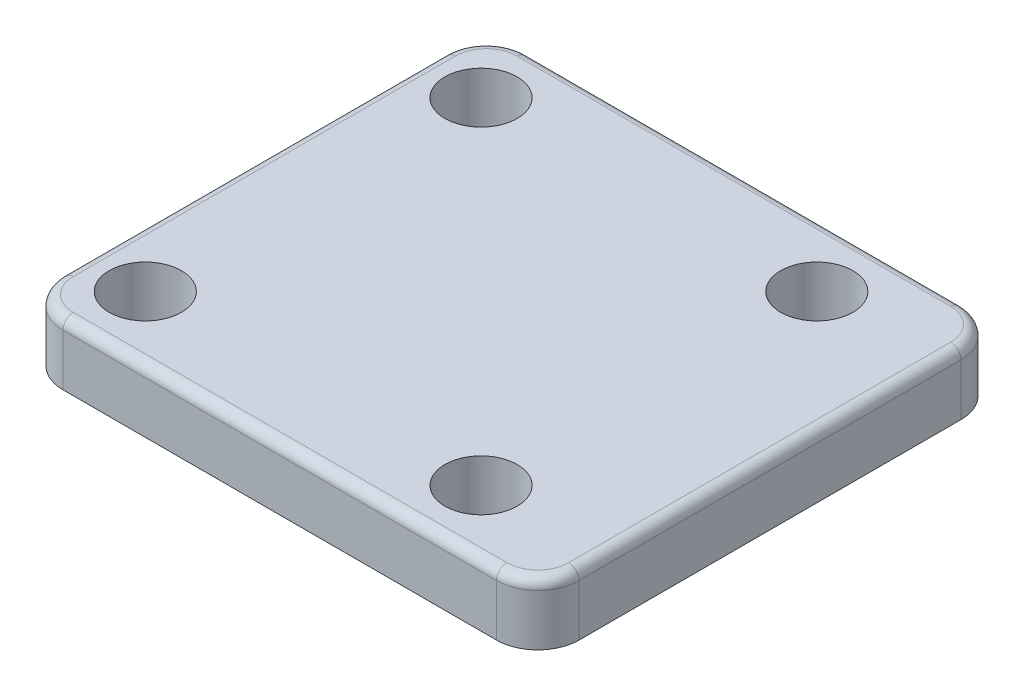
SolidWorks part; units mm, degrees
ref_plane "Front Plane" through (0, 0, 0) normal (0, 0, 1) x (1, 0, 0)
ref_plane "Top Plane" through (0, 0, 0) normal (0, 1, 0) x (1, 0, 0)
ref_plane "Right Plane" through (0, 0, 0) normal (1, 0, 0) x (0, 0, -1)
sketch "Sketch1" plane through (0, 0, 0) normal (0, 1, 0) x (1, 0, 0)
  line L1 (24, -22.5) -> (-18, -22.5)
  line L2 (28, -18.5) -> (28, 18.5)
  line L3 (24, 22.5) -> (-18, 22.5)
  line L4 (-22, -18.5) -> (-22, 18.5)
  line L5 (28, -22.5) -> (-22, 22.5) construction
  line L6 (28, 22.5) -> (-22, -22.5) construction
  arc A0 (24, -22.5) -> (28, -18.5) centre (24, -18.5) ccw
  arc A1 (-18, -22.5) -> (-22, -18.5) centre (-18, -18.5) cw
  arc A2 (28, 18.5) -> (24, 22.5) centre (24, 18.5) ccw
  arc A3 (-18, 22.5) -> (-22, 18.5) centre (-18, 18.5) ccw
  point P0 (3, 0)
  dimension "D5" = 4
  dimension "D1" = 50
  dimension "D2" = 45
  dimension "D3" = 22
  dimension "D4" = 22.5
extrude "Boss-Extrude1" add sketch "Sketch1" along normal blind 6
fillet "Fillet1" radius 1 8 edges at (3, 6, 22.5) (-20.8284, 6, 21.3284) (-22, 6, 0) (-20.8284, 6, -21.3284) (3, 6, -22.5) (26.8284, 6, -21.3284) (28, 6, 0) (26.8284, 6, 21.3284)
sketch "Sketch2" plane through (0, 6, 0) normal (0, 1, 0) x (1, 0, 0)
  circle A0 centre (0, 0) radius 16
  dimension "D1" = 32
extrude "Boss-Extrude6" add sketch "Sketch2" against normal blind 8
chamfer "Chamfer3" distance 1 angle 45 1 edges at (0, -2, 16)
sketch "Sketch3" plane through (0, 6, 0) normal (0, 1, 0) x (1, 0, 0)
  line L0 (0, 0) -> (-23, 0) construction
  line L1 (0, 0) -> (-16.2635, 16.2635) construction
  circle A0 centre (0, 0) radius 23 construction
  circle A1 centre (-16.2635, 16.2635) radius 3.5
  circle A2 centre (0, 0) radius 23 construction
  circle A3 centre (16.2635, 16.2635) radius 3.5
  circle A4 centre (0, 0) radius 23 construction
  circle A5 centre (16.2635, -16.2635) radius 3.5
  circle A6 centre (0, 0) radius 23 construction
  circle A7 centre (-16.2635, -16.2635) radius 3.5
  point P18 (0, 0)
  dimension "D1" = 46
  dimension "D2" = 45
  dimension "D3" = 7
  dimension "D4" = 4
extrude "Cut-Extrude1" cut sketch "Sketch3" against normal through all
